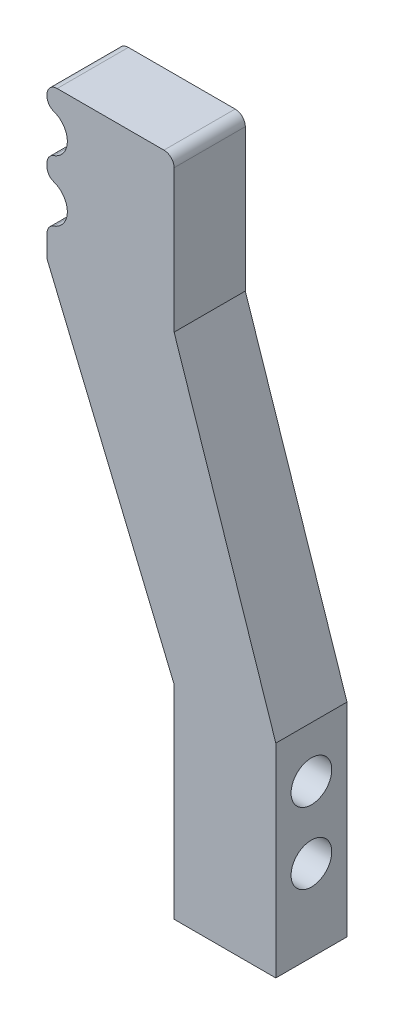
SolidWorks part; units mm, degrees
ref_plane "Front Plane" through (0, 0, 0) normal (0, 0, 1) x (1, 0, 0)
ref_plane "Top Plane" through (0, 0, 0) normal (0, 1, 0) x (1, 0, 0)
ref_plane "Right Plane" through (0, 0, 0) normal (1, 0, 0) x (0, 0, -1)
sketch "Sketch1" plane through (0, 0, 0) normal (0, 0, 1) x (1, 0, 0)
  line L13 (-100.0843, 339.2989) -> (-100.0843, 139.2989)
  line L14 (-215.0843, 789.2989) -> (-110.0843, 789.2989)
  line L15 (-225.0843, 779.2989) -> (-225.0843, 639.2989)
  line L17 (-0.0843, 339.2989) -> (-0.0843, 139.2989)
  line L18 (-100.0843, 779.2989) -> (-100.0843, 639.2989)
  line L19 (-0.0843, 139.2989) -> (-100.0843, 139.2989)
  line L22 (-0.0843, 339.2989) -> (-100.0843, 639.2989)
  line L23 (-100.0843, 339.2989) -> (-225.0843, 639.2989)
  arc A0 (-100.0843, 779.2989) -> (-110.0843, 789.2989) centre (-110.0843, 779.2989) ccw
  arc A1 (-225.0843, 779.2989) -> (-215.0843, 789.2989) centre (-215.0843, 779.2989) cw
  dimension "D1" = 10
  dimension "D2" = 10
extrude "Boss-Extrude1" add sketch "Sketch1" along normal blind 70
sketch "Sketch2" plane through (-0.0843, 0, 0) normal (1, 0, 0) x (0, 0, -1)
  circle A1 centre (-35, 289.2989) radius 20
  circle A2 centre (-35, 219.2989) radius 20
extrude "Cut-Extrude1" cut sketch "Sketch2" against normal blind 192
sketch "Sketch3" plane through (0, 0, 70) normal (0, 0, 1) x (1, 0, 0)
  line L2 (-225.0843, 769.2989) -> (-225.0843, 749.2989)
  line L3 (-225.0843, 779.2989) -> (-225.0843, 639.2989) construction
  line L4 (-225.0843, 749.2989) -> (-225.0843, 729.2989)
  line L5 (-225.0843, 689.2989) -> (-225.0843, 669.2989)
  line L6 (-225.0843, 709.2989) -> (-225.0843, 689.2989)
  arc A0 (-225.0843, 729.2989) -> (-225.0843, 769.2989) centre (-225.0843, 749.2989) ccw
  arc A1 (-225.0843, 669.2989) -> (-225.0843, 709.2989) centre (-225.0843, 689.2989) ccw
extrude "Cut-Extrude2" cut sketch "Sketch3" against normal blind 192
sketch "Sketch4" plane through (0, 0, 70) normal (0, 0, 1) x (1, 0, 0)
  line L0 (-218.4177, 730.4427) -> (-225.0843, 729.2989)
  line L3 (-225.0843, 729.2989) -> (-225.0843, 721.0146)
  line L4 (-225.0843, 717.5831) -> (-225.0843, 709.2989)
  line L5 (-225.0843, 709.2989) -> (-218.4177, 708.155)
  line L6 (-218.4177, 670.4427) -> (-225.0843, 669.2989)
  line L7 (-225.0843, 669.2989) -> (-225.0843, 661.0146)
  line L8 (-225.0843, 777.5831) -> (-225.0843, 769.2989)
  line L9 (-225.0843, 769.2989) -> (-218.4177, 768.155)
  arc A2 (-225.0843, 661.0146) -> (-218.4177, 670.4427) centre (-215.0843, 661.0146) cw
  arc A3 (-225.0843, 721.0146) -> (-218.4177, 730.4427) centre (-215.0843, 721.0146) cw
  arc A4 (-218.4177, 708.155) -> (-225.0843, 717.5831) centre (-215.0843, 717.5831) cw
  arc A5 (-218.4177, 768.155) -> (-225.0843, 777.5831) centre (-215.0843, 777.5831) cw
  point P17 (-225.0843, 669.2989)
  point P20 (-225.0843, 729.2989)
  point P23 (-225.0843, 709.2989)
  point P26 (-225.0843, 769.2989)
extrude "Cut-Extrude3" cut sketch "Sketch4" against normal blind 192
